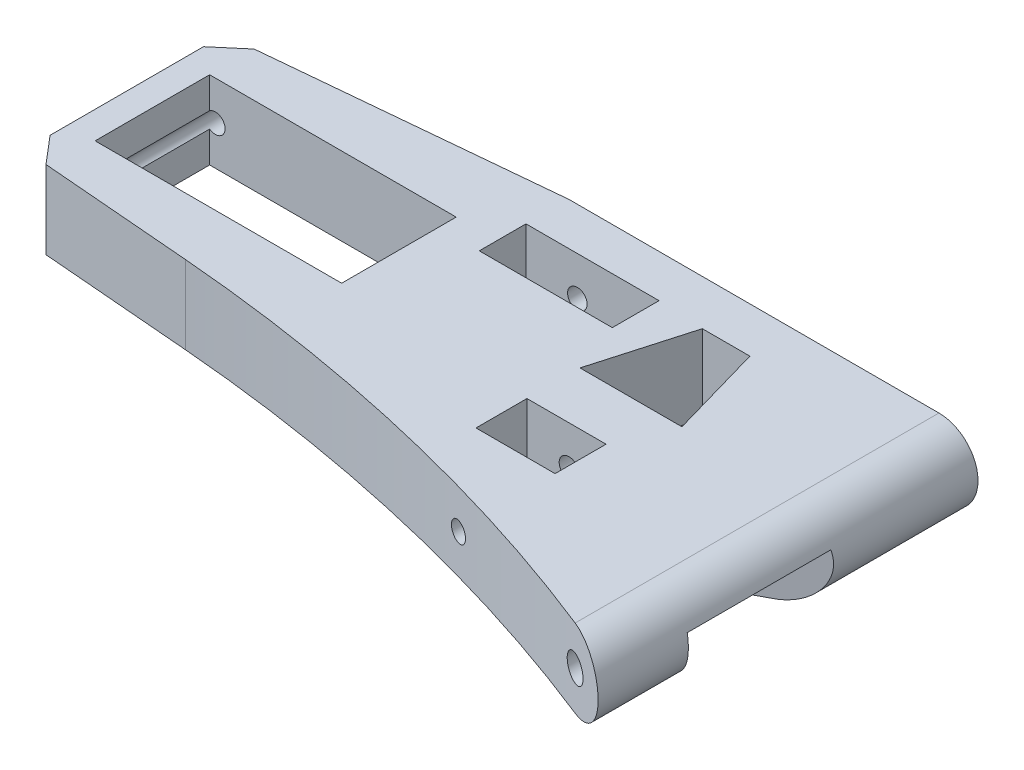
SolidWorks part; units mm, degrees
ref_plane "Front Plane" through (0, 0, 0) normal (0, 0, 1) x (1, 0, 0)
ref_plane "Top Plane" through (0, 0, 0) normal (0, 1, 0) x (1, 0, 0)
ref_plane "Right Plane" through (0, 0, 0) normal (1, 0, 0) x (0, 0, -1)
sketch "Sketch1" plane through (0, 0, 0) normal (0, 1, 0) x (1, 0, 0)
  line L0 (0, 58.1849) -> (0, -59.0181) construction
  line L1 (-25.4, 34.3767) -> (-67.6656, 34.3767)
  line L2 (-67.6656, 34.3767) -> (-86.5378, 34.3767)
  line L3 (-86.5378, 34.3767) -> (-129.54, 30.3127)
  line L4 (-129.54, 30.3127) -> (-133.6294, 26.8329)
  line L5 (-133.6294, 26.8329) -> (-133.6294, 3.8967)
  line L6 (-133.6294, 3.8967) -> (-130.1496, -0.1927)
  line L7 (-130.1496, -0.1927) -> (-107.4238, -2.0695)
  line L8 (-25.4, -22.4116) -> (-25.4, 34.3767)
  line L9 (-63.9064, -2.1597) -> (-65.5879, -8.9393) construction
  line L10 (-129.54, 23.6579) -> (-92.6846, 23.6579)
  line L11 (-129.54, 23.6579) -> (-129.54, 6.5383)
  line L12 (-129.54, 6.5383) -> (-92.6846, 6.5383)
  line L13 (-92.6846, 23.6579) -> (-92.6846, 6.5383)
  line L14 (-86.5916, 28.0013) -> (-66.7034, 28.0013)
  line L15 (-86.5916, 28.0013) -> (-86.5916, 21.0163)
  line L16 (-86.5916, 21.0163) -> (-66.7034, 21.0163)
  line L17 (-66.7034, 28.0013) -> (-66.7034, 21.0163)
  line L18 (-63.9064, 5.4603) -> (-52.0827, 5.4603)
  line L19 (-63.9064, 5.4603) -> (-63.9064, -2.1597)
  line L20 (-63.9064, -2.1597) -> (-52.0827, -2.1597)
  line L21 (-52.0827, 5.4603) -> (-52.0827, -2.1597)
  line L22 (-80.6438, -5.2051) -> (-46.5422, -13.6631) construction
  line L23 (-63.9064, 13.3847) -> (-48.6664, 13.3847)
  line L24 (-48.6664, 13.3847) -> (-52.7304, 27.6087)
  line L25 (-52.7304, 27.6087) -> (-59.8424, 27.6087)
  line L26 (-59.8424, 27.6087) -> (-63.9064, 13.3847)
  line L27 (-56.2864, 27.6087) -> (-56.2864, 13.3847) construction
  arc A0 (-107.4238, -2.0695) -> (-25.4, -22.4116) centre (-129.1572, -265.2423) cw
  dimension "D2" = 108.2294
  dimension "D3" = 22.9362
  dimension "D4" = 30.5054
  dimension "D5" = 4.0894
  dimension "D6" = 6.6548
  dimension "D7" = 17.1196
  dimension "D8" = 36.8554
  dimension "D9" = 47.0916
  dimension "D10" = 6.3754
  dimension "D11" = 19.8882
  dimension "D12" = 6.985
  dimension "D13" = 11.8237
  dimension "D14" = 7.62
  dimension "D15" = 69.723
  dimension "D16" = 25.4
  dimension "D17" = 6.985
  dimension "D18" = 4.064
  dimension "D19" = 18.8722
  dimension "D20" = 7.112
  dimension "D21" = 15.24
  dimension "D22" = 14.224
extrude "Boss-Extrude1" add sketch "Sketch1" along normal blind 11.684
sketch "Sketch2" plane through (0, 0, 0) normal (0, 0, 1) x (1, 0, 0)
  line L0 (0, 33.0453) -> (0, -31.8853) construction
  line L1 (57.7926, 5.842) -> (-46.4651, 5.842) construction
  line L6 (-25.4, 11.684) -> (-107.4238, 11.684) construction
  line L7 (-107.4238, 0) -> (-25.4, 0) construction
  line L8 (-25.4, 11.684) -> (-25.4, 0) construction
  line L9 (-31.242, 11.684) -> (-25.4, 11.684)
  line L10 (-25.4, 11.684) -> (-25.4, 5.842)
  line L11 (-31.242, 0) -> (-25.4, 0)
  line L12 (-25.4, 0) -> (-25.4, 5.842)
  arc A0 (-31.242, 11.684) -> (-31.242, 0) centre (-31.242, 5.842) cw
extrude "Cut-Extrude7" cut sketch "Sketch2" against normal through all both and the other way through all contours L9 A0 L10 | L12 A0 L11
sketch "Sketch3" plane through (0, 0, 0) normal (0, 0, 1) x (1, 0, 0)
  line L0 (-128.6891, 11.684) -> (-128.6891, 0) construction
  line L1 (-130.1496, 11.684) -> (-107.4238, 11.684) construction
  line L2 (-130.1496, 0) -> (-107.4238, 0) construction
  line L3 (-130.1496, 11.684) -> (-130.1496, 0) construction
  circle A0 centre (-128.6891, 5.842) radius 1.4605
  dimension "D1" = 2.921
extrude "Cut-Extrude8" cut sketch "Sketch3" against normal through all
sketch "Sketch4" plane through (0, 0, -34.3767) normal (0, 0, -1) x (-1, 0, 0)
  line L0 (78.9178, 11.684) -> (78.9178, 0) construction
  line L1 (31.242, 11.684) -> (86.5378, 11.684) construction
  line L2 (31.242, 0) -> (86.5378, 0) construction
  line L3 (86.5378, 11.684) -> (86.5378, 0) construction
  circle A0 centre (78.9178, 5.842) radius 1.4605
  dimension "D2" = 2.921
  dimension "D1" = 7.62
extrude "Cut-Extrude9" cut sketch "Sketch4" against normal blind 18.034
sketch "Sketch5" plane through (0, 0, 0) normal (0, 0, 1) x (1, 0, 0)
  line L0 (-57.6326, 11.684) -> (-57.6326, 0) construction
  line L1 (-31.242, 11.684) -> (-107.4238, 11.684) construction
  line L2 (-107.4238, 0) -> (-31.242, 0) construction
  arc A0 (-31.242, 0) -> (-31.242, 11.684) centre (-31.242, 5.842) ccw construction
  circle A1 centre (-57.6326, 5.842) radius 1.4605
  dimension "D2" = 2.921
  dimension "D1" = 26.3906
extrude "Cut-Extrude10" cut sketch "Sketch5" against normal mid plane 32.639
sketch "Sketch6" plane through (0, 0, 0) normal (0, 0, 1) x (1, 0, 0)
  line L0 (-31.242, 11.684) -> (-31.242, 0) construction
  line L1 (-31.242, 11.684) -> (-107.4238, 11.684) construction
  line L2 (-107.4238, 0) -> (-31.242, 0) construction
  circle A0 centre (-31.242, 5.842) radius 1.9685
  arc A1 (-31.242, 0) -> (-31.242, 11.684) centre (-31.242, 5.842) ccw construction
  dimension "D1" = 3.937
extrude "Cut-Extrude11" cut sketch "Sketch6" against normal through all both and the other way through all
sketch "Sketch8" plane through (0, 0, 0) normal (0, -1, 0) x (1, 0, 0)
  line L0 (-25.4, -34.3767) -> (-25.4, 22.4116) construction
  line L1 (-34.1275, 5.5507) -> (-23.2585, 9.7495)
  line L2 (-23.2585, 9.7495) -> (-23.2585, -12.8102)
  line L3 (-34.9349, -7.7033) -> (-23.2585, -13.9362)
  line L4 (-23.2585, -13.9362) -> (-23.2585, -12.8102)
  arc A0 (-34.1275, 5.5507) -> (-34.9349, -7.7033) centre (-31.496, -1.2612) ccw
  dimension "D1" = 23.6728
  dimension "D2" = 6.096
  dimension "D3" = 14.605
extrude "Cut-Extrude12" cut sketch "Sketch8" against normal blind 7.62
